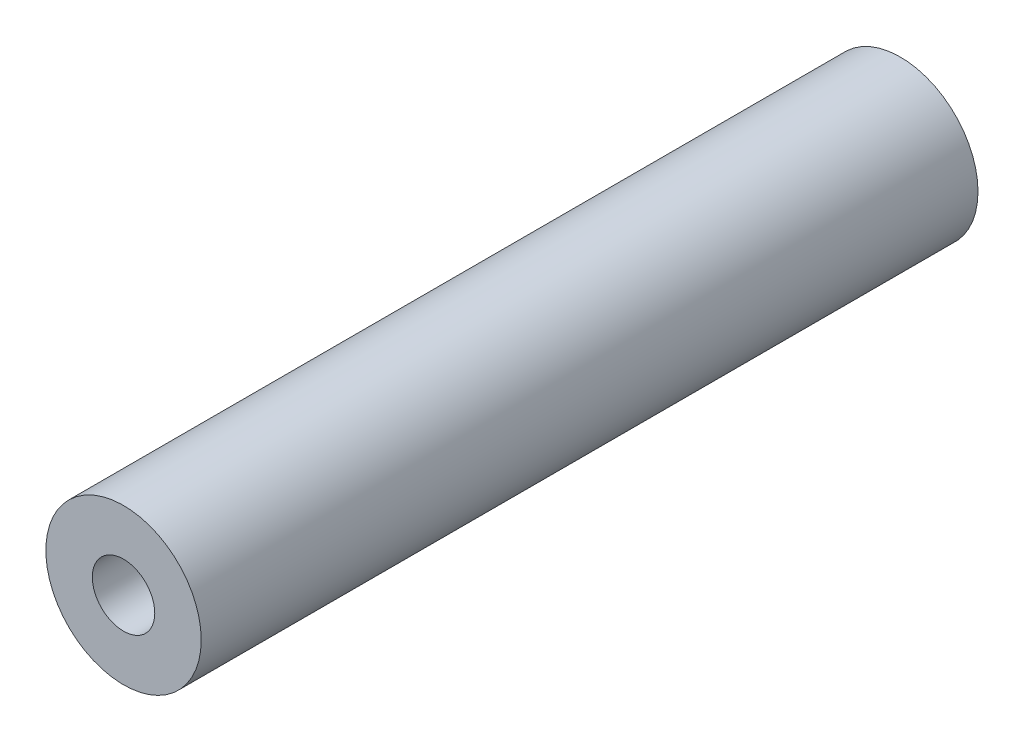
SolidWorks part; units mm, degrees
material "6061-T6 (SS)"
ref_plane "Front Plane" through (0, 0, 0) normal (0, 0, 1) x (1, 0, 0)
ref_plane "Top Plane" through (0, 0, 0) normal (0, 1, 0) x (1, 0, 0)
ref_plane "Right Plane" through (0, 0, 0) normal (1, 0, 0) x (0, 0, -1)
sketch "Sketch1" plane through (0, 0, 0) normal (0, 0, 1) x (1, 0, 0)
  circle A0 centre (0, 0) radius 6.35
  dimension "D1" = 12.7
extrude "Boss-Extrude1" add sketch "Sketch1" along normal mid plane 63.5
hole_wizard "1/4-20 Tapped Hole1" positions "3DSketch1" profile "Sketch2" tap size "1/4-20" standard "ANSI Inch"
sketch3d "3DSketch1"
  line L0 (0, 0, 31.75) -> (0, 0, -31.75) construction
  point P0 (0, 0, 31.75)
  point P4 (0, 0, -31.75)
sketch "Sketch2" plane through (0, 0, 31.75) normal (1, 0, 0) x (0, -1, 0)
  line L0 (0, 0) -> (0, 18.0438)
  line L1 (0, 18.0438) -> (2.5527, 16.51)
  line L2 (2.5527, 16.51) -> (2.5527, 0)
  line L5 (2.5527, 0) -> (0, 0)
  line L10 (0, 18.0438) -> (-2.5527, 16.51) construction
  line L11 (0, -6.35) -> (0, 107.95) construction
  dimension "Tap Drill Dia." = 5.1054
  dimension "Tap Drill Depth" = 16.51
  dimension "Drill Angle" = 118
cosmetic thread "Hole Thread1" parameters "D1"=12.7, "D2"=6.35
cosmetic thread "Hole Thread2" parameters "D1"=12.7, "D2"=6.35
